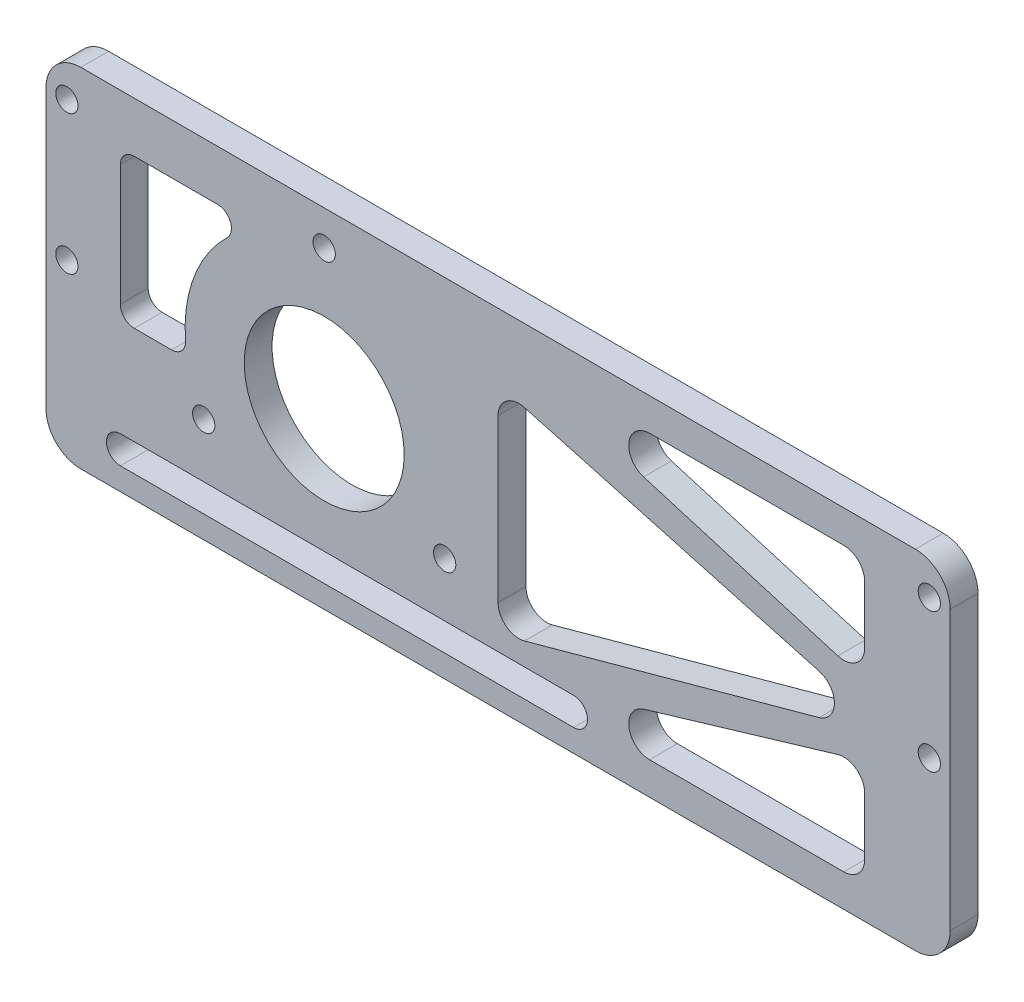
SolidWorks part; units mm, degrees
material "Hexcel AS4C (3000 丝)"
ref_plane "前视基准面" through (0, 0, 0) normal (0, 0, 1) x (1, 0, 0)
ref_plane "上视基准面" through (0, 0, 0) normal (0, 1, 0) x (1, 0, 0)
ref_plane "右视基准面" through (0, 0, 0) normal (1, 0, 0) x (0, 0, -1)
sketch "草图1" plane through (0, 0, 0) normal (0, 0, 1) x (1, 0, 0)
  line L0 (0, 0) -> (-25, 0) construction
  line L1 (-65, 25) -> (65, 25)
  line L2 (-65, 25) -> (-65, -25)
  line L3 (-65, -25) -> (65, -25)
  line L4 (65, 25) -> (65, -25)
  line L5 (-65, 25) -> (65, -25) construction
  line L6 (-65, -25) -> (65, 25) construction
  circle A0 centre (-25, 0) radius 11.5
  circle A1 centre (-25, 0) radius 20 construction
  circle A2 centre (-25, 20) radius 1.6
  circle A3 centre (-7.6795, -10) radius 1.6
  circle A4 centre (-42.3205, -10) radius 1.6
  point P12 (-25, 0)
  dimension "D1" = 23
  dimension "D2" = 40
  dimension "D3" = 3.2
  dimension "D5" = 50
  dimension "D6" = 130
  dimension "D7" = 25
  dimension "D4" = 3
extrude "凸台-拉伸1" add sketch "草图1" along normal mid plane 4
sketch "草图2" plane through (0, 0, 2) normal (0, 0, 1) x (1, 0, 0)
  line L0 (-62, 20) -> (-62, 0) construction
  line L1 (-65, 25) -> (-65, -25) construction
  line L4 (0, 0) -> (0, 37.0805) construction
  line L5 (65, 25) -> (-65, 25) construction
  circle A0 centre (-62, 0) radius 1.6
  circle A1 centre (-62, 20) radius 1.6
  circle A2 centre (62, 0) radius 1.6
  circle A3 centre (62, 20) radius 1.6
  dimension "D2" = 3.2
  dimension "D4" = 5
  dimension "D1" = 3
  dimension "D3" = 20
extrude "切除-拉伸1" cut sketch "草图2" against normal through all
fillet "圆角1" radius 5 4 edges at (65, 25, 0) (65, -25, 0) (-65, -25, 0) (-65, 25, 0)
sketch "草图3" plane through (0, 0, 2) normal (0, 0, 1) x (1, 0, 0)
  line L0 (0, 0) -> (76.9117, 0) construction
  line L1 (0, -15.5742) -> (0, 15.5742)
  line L2 (0, 15.5742) -> (56.6749, 0)
  line L3 (56.6749, 0) -> (0, -15.5742)
  line L4 (52.7049, -20.329) -> (1.1831, -20.329)
  line L5 (1.1831, -20.329) -> (52.7049, -4.9967)
  line L6 (52.7049, -4.9967) -> (52.7049, -20.329)
  line L7 (1.1831, 20.329) -> (52.7049, 4.9967)
  line L8 (52.7049, 20.329) -> (1.1831, 20.329)
  line L9 (52.7049, 4.9967) -> (52.7049, 20.329)
extrude "切除-拉伸2" cut sketch "草图3" against normal through all
fillet "圆角2" radius 3 9 edges at (56.6749, 0, 0) (1.1831, -20.329, 0) (52.7049, -4.9967, 0) (52.7049, -20.329, 0) (52.7049, 4.9967, 0) (1.1831, 20.329, 0) (52.7049, 20.329, 0) (0, -15.5742, 0) (0, 15.5742, 0)
sketch "草图4" plane through (0, 0, 2) normal (0, 0, 1) x (1, 0, 0)
  line L0 (-34.1802, 17.7686) -> (-54.3084, 17.7686)
  line L1 (-54.3084, 17.7686) -> (-54.3084, -3.6563)
  line L2 (-54.3084, -3.6563) -> (-44.663, -3.6563)
  line L3 (-54.3084, -19.7708) -> (10.8579, -19.7708) construction
  line L4 (-54.3084, -17.7708) -> (10.8579, -17.7708)
  line L5 (-54.3084, -21.7708) -> (10.8579, -21.7708)
  arc A0 (-34.1802, 17.7686) -> (-44.663, -3.6563) centre (-25, 0) ccw
  arc A1 (-54.3084, -17.7708) -> (-54.3084, -21.7708) centre (-54.3084, -19.7708) ccw
  arc A2 (10.8579, -21.7708) -> (10.8579, -17.7708) centre (10.8579, -19.7708) ccw
  point P8 (-21.7252, -19.7708)
  dimension "D1" = 20
  dimension "D2" = 2
extrude "切除-拉伸3" cut sketch "草图4" against normal through all
fillet "圆角3" radius 2 4 edges at (-54.3084, -3.6563, 0) (-44.663, -3.6563, 0) (-54.3084, 17.7686, 0) (-34.1802, 17.7686, 0)
